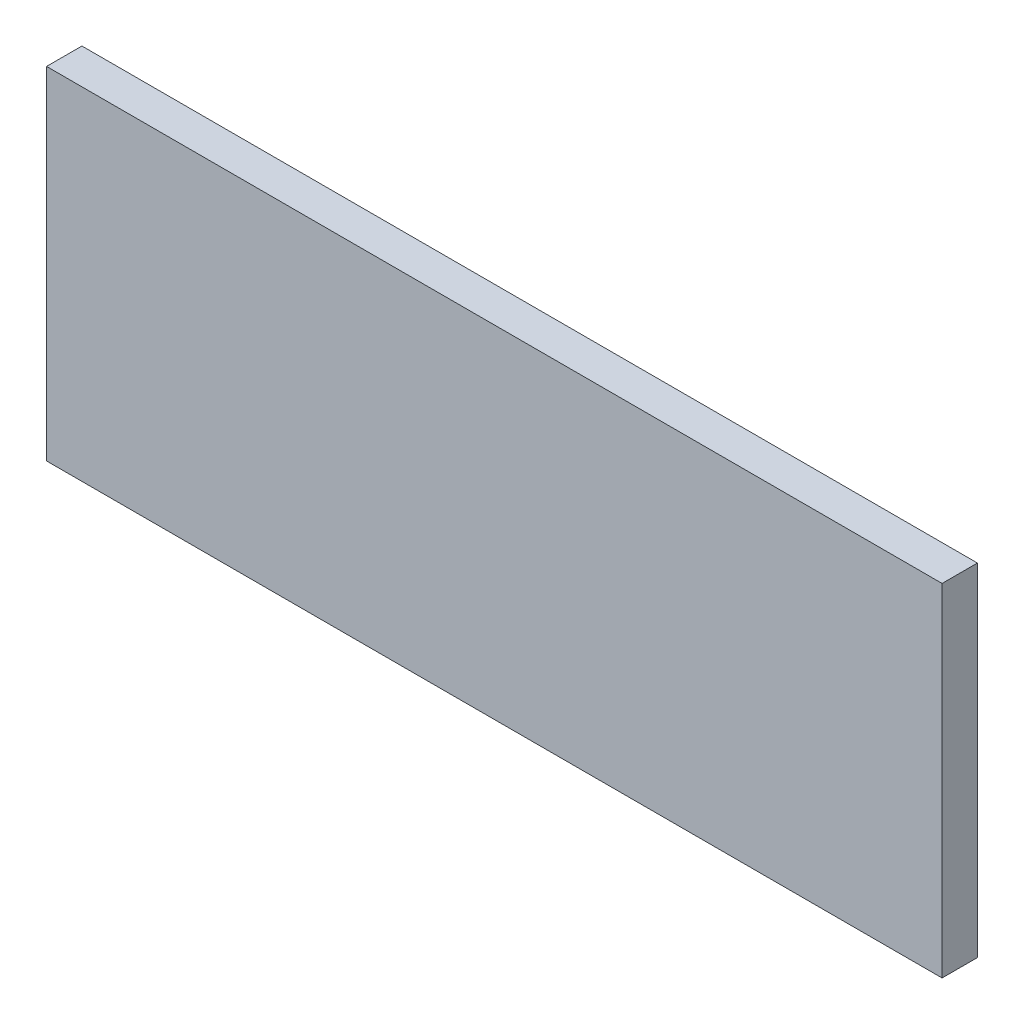
SolidWorks part; units mm, degrees
ref_plane "Front Plane" through (0, 0, 0) normal (0, 0, 1) x (1, 0, 0)
ref_plane "Top Plane" through (0, 0, 0) normal (0, 1, 0) x (1, 0, 0)
ref_plane "Right Plane" through (0, 0, 0) normal (1, 0, 0) x (0, 0, -1)
sketch "Sketch1" plane through (0, 0, 0) normal (0, 0, 1) x (1, 0, 0)
  line L1 (0, 0) -> (482.6, 0)
  line L2 (0, 0) -> (0, 184.15)
  line L3 (0, 184.15) -> (482.6, 184.15)
  line L4 (482.6, 0) -> (482.6, 184.15)
  dimension "D1" = 482.6
  dimension "D2" = 184.15
extrude "Boss-Extrude1" add sketch "Sketch1" along normal blind 19.05
